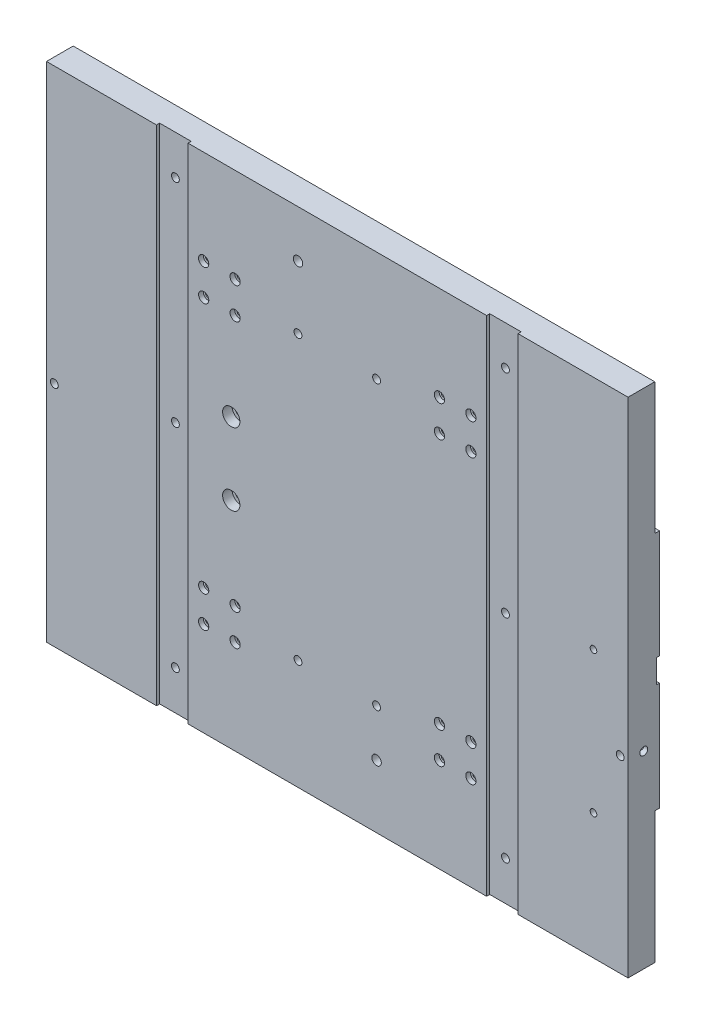
SolidWorks part; units mm, degrees
material "铝材"
ref_plane "前基準面" through (0, 0, 0) normal (0, 0, 1) x (1, 0, 0)
ref_plane "上基準面" through (0, 0, 0) normal (0, 1, 0) x (1, 0, 0)
ref_plane "右基準面" through (0, 0, 0) normal (1, 0, 0) x (0, 0, -1)
sketch "草图1" plane through (0, 0, 0) normal (0, 0, 1) x (1, 0, 0)
  line L1 (0, 0) -> (370, 0)
  line L2 (0, 0) -> (0, 320)
  line L3 (0, 320) -> (370, 320)
  line L4 (370, 0) -> (370, 320)
  dimension "D1" = 370
  dimension "D2" = 320
extrude "凸台-拉伸1" add sketch "草图1" along normal blind 20
sketch "草图2" plane through (370, 0, 0) normal (1, 0, 0) x (0, 0, -1)
  line L0 (0, 0) -> (0, 320) construction
  line L1 (0, 0) -> (-3, 0)
  line L2 (0, 0) -> (0, 83.6)
  line L3 (0, 83.6) -> (-3, 83.6)
  line L4 (-3, 0) -> (-3, 83.6)
  line L5 (0, 160) -> (-20, 160) construction
  line L6 (-20, 0) -> (-20, 320) construction
  line L7 (-3, 320) -> (-3, 236.4)
  line L8 (0, 236.4) -> (-3, 236.4)
  line L9 (0, 320) -> (0, 236.4)
  line L10 (0, 320) -> (-3, 320)
  dimension "D1" = 152.8
  dimension "D3" = 3
extrude "切除-拉伸1" cut sketch "草图2" against normal through all
sketch "草图3" plane through (0, 0, 0) normal (0, -1, 0) x (1, 0, 0)
  line L0 (0, 20) -> (370, 20) construction
  line L1 (230, 20) -> (140, 20)
  line L2 (230, 20) -> (230, 18)
  line L3 (230, 18) -> (140, 18)
  line L4 (140, 20) -> (140, 18)
  line L5 (185, 20) -> (185, 0) construction
  dimension "D1" = 2
  dimension "D2" = 90
extrude "切除-拉伸2" cut sketch "草图3" against normal through all
sketch "草图4" plane through (0, 0, 0) normal (0, -1, 0) x (1, 0, 0)
  line L0 (0, 20) -> (140, 20) construction
  line L1 (70, 20) -> (90, 20)
  line L2 (70, 20) -> (70, 18)
  line L3 (70, 18) -> (90, 18)
  line L4 (90, 20) -> (90, 18)
  line L5 (185, 3) -> (185, 18) construction
  line L6 (0, 3) -> (370, 3) construction
  line L7 (140, 18) -> (230, 18) construction
  line L8 (280, 20) -> (280, 18)
  line L9 (300, 18) -> (280, 18)
  line L10 (300, 20) -> (300, 18)
  line L11 (300, 20) -> (280, 20)
  dimension "D1" = 190
  dimension "D2" = 20
  dimension "D3" = 2
extrude "切除-拉伸3" cut sketch "草图4" against normal through all
sketch "草图5" plane through (370, 0, 0) normal (1, 0, 0) x (0, 0, -1)
  line L0 (0, 83.6) -> (0, 236.4) construction
  line L1 (0, 152.5) -> (-2, 152.5)
  line L2 (0, 152.5) -> (0, 167.5)
  line L3 (0, 167.5) -> (-2, 167.5)
  line L4 (-2, 152.5) -> (-2, 167.5)
  line L5 (0, 160) -> (-12.4315, 160) construction
  dimension "D1" = 2
  dimension "D2" = 15
sketch "草图6" plane through (0, 0, 18) normal (0, 0, 1) x (1, 0, 0)
  line L4 (140, 0) -> (230, 0)
  line L5 (230, 0) -> (230, 320)
  line L6 (230, 320) -> (140, 320)
  line L7 (140, 320) -> (140, 0)
  line L8 (140, 0) -> (230, 0)
  line L9 (230, 0) -> (230, 320)
  line L10 (230, 320) -> (140, 320)
  line L11 (140, 320) -> (140, 0)
  dimension "D1" = 0
extrude "凸台-拉伸2" add sketch "草图6" along normal up to surface (2 mm away) up to face at (255, 160, 20)
extrude "切除-拉伸4" cut sketch "草图5" against normal through all
sketch "草图7" plane through (0, 0, 0) normal (-1, 0, 0) x (0, 0, 1)
  line L0 (20, 320) -> (20, 0) construction
  line L1 (20, 0) -> (3, 0) construction
  circle A0 centre (10, 145) radius 2.5
  dimension "D2" = 5
  dimension "D3" = 145
  dimension "D1" = 10
extrude "切除-拉伸5" cut sketch "草图7" against normal blind 15
hole_wizard "M6 螺纹孔1" positions "草图9" profile "草图8" tap size "M6" standard "ISO"
sketch "草图9" plane through (0, 0, 20) normal (0, 0, 1) x (1, 0, 0)
  line L0 (0, 320) -> (0, 0) construction
  line L1 (0, 0) -> (70, 0) construction
  point P0 (5, 145)
  dimension "D1" = 5
  dimension "D2" = 145
sketch "草图8" plane through (5, 145, 20) normal (1, 0, 0) x (0, -1, 0)
  line L0 (0, 0) -> (0, 16.5022)
  line L1 (0, 16.5022) -> (2.5, 15)
  line L2 (2.5, 15) -> (2.5, 0)
  line L5 (2.5, 0) -> (0, 0)
  line L10 (0, 16.5022) -> (-2.5, 15) construction
  line L11 (0, -6.35) -> (0, 107.95) construction
  dimension "螺纹孔钻头直径" = 5
  dimension "螺纹孔钻头深度" = 15
  dimension "导头角度" = 118
cosmetic thread "孔螺蚊线1" parameters "D1"=12, "D2"=6
sketch "草图10" plane through (370, 0, 0) normal (1, 0, 0) x (0, 0, -1)
  line L0 (-20, 0) -> (-20, 320) construction
  line L1 (-20, 0) -> (-3, 0) construction
  circle A2 centre (-10, 120) radius 2.5
  dimension "D1" = 10
  dimension "D2" = 5
  dimension "D3" = 120
extrude "切除-拉伸6" cut sketch "草图10" against normal blind 15
hole_wizard "M6 螺纹孔2" positions "草图12" profile "草图11" tap size "M6" standard "ISO"
sketch "草图12" plane through (0, 0, 20) normal (0, 0, 1) x (1, 0, 0)
  line L0 (370, 0) -> (370, 320) construction
  line L1 (300, 0) -> (370, 0) construction
  point P0 (365, 120)
  dimension "D1" = 5
  dimension "D2" = 120
sketch "草图11" plane through (365, 120, 20) normal (1, 0, 0) x (0, -1, 0)
  line L0 (0, 0) -> (0, 16.5022)
  line L1 (0, 16.5022) -> (2.5, 15)
  line L2 (2.5, 15) -> (2.5, 0)
  line L5 (2.5, 0) -> (0, 0)
  line L10 (0, 16.5022) -> (-2.5, 15) construction
  line L11 (0, -6.35) -> (0, 107.95) construction
  dimension "螺纹孔钻头直径" = 5
  dimension "螺纹孔钻头深度" = 15
  dimension "导头角度" = 118
cosmetic thread "孔螺蚊线2" parameters "D1"=12, "D2"=6
sketch "草图13" plane through (0, 0, 20) normal (0, 0, 1) x (1, 0, 0)
  circle A0 centre (210, 40) radius 3
  circle A1 centre (160, 290) radius 3
extrude "切除-拉伸7" cut sketch "草图13" against normal through all
hole_wizard "M6 螺纹孔3" positions "草图15" profile "草图14" tap size "M6" standard "ISO"
sketch "草图15" plane through (0, 0, 20) normal (0, 0, 1) x (1, 0, 0)
  point P0 (160, 70)
  point P4 (210, 70)
  point P7 (160, 250)
  point P10 (210, 250)
  point P13 (290, 25)
  point P16 (290, 160)
  point P19 (290, 295)
  point P22 (80, 295)
  point P25 (80, 160)
  point P28 (80, 25)
sketch "草图14" plane through (160, 70, 20) normal (1, 0, 0) x (0, -1, 0)
  line L0 (0, 0) -> (0, 16.5022)
  line L1 (0, 16.5022) -> (2.5, 15)
  line L2 (2.5, 15) -> (2.5, 0)
  line L5 (2.5, 0) -> (0, 0)
  line L10 (0, 16.5022) -> (-2.5, 15) construction
  line L11 (0, -6.35) -> (0, 107.95) construction
  dimension "螺纹孔钻头直径" = 5
  dimension "螺纹孔钻头深度" = 15
  dimension "导头角度" = 118
cosmetic thread "孔螺蚊线3" parameters "D1"=12, "D2"=6
cosmetic thread "孔螺蚊线4" parameters "D1"=12, "D2"=6
cosmetic thread "孔螺蚊线5" parameters "D1"=12, "D2"=6
cosmetic thread "孔螺蚊线6" parameters "D1"=12, "D2"=6
cosmetic thread "孔螺蚊线7" parameters "D1"=12, "D2"=6
cosmetic thread "孔螺蚊线8" parameters "D1"=12, "D2"=6
cosmetic thread "孔螺蚊线9" parameters "D1"=12, "D2"=6
cosmetic thread "孔螺蚊线10" parameters "D1"=12, "D2"=6
cosmetic thread "孔螺蚊线11" parameters "D1"=12, "D2"=6
cosmetic thread "孔螺蚊线12" parameters "D1"=12, "D2"=6
hole_wizard "M3 六角凹头螺钉的柱形沉头孔1" positions "草图17" profile "草图16" counterbore size "M3" standard "ISO" end condition through all
sketch "草图17" plane through (0, 0, 20) normal (0, 0, 1) x (1, 0, 0)
  point P0 (270, 80)
  point P1 (250, 60)
  point P8 (250, 80)
  point P11 (270, 60)
  point P14 (120, 60)
  point P17 (100, 60)
  point P20 (100, 80)
  point P23 (120, 80)
sketch "草图16" plane through (270, 80, 20) normal (1, 0, 0) x (0, -1, 0)
  line L0 (0, 0) -> (0, 20)
  line L1 (0, 20) -> (1.8, 20)
  line L3 (1.8, 20) -> (1.8, 3)
  line L4 (1.8, 3) -> (3.25, 3)
  line L5 (3.25, 3) -> (3.25, 0)
  line L7 (3.25, 0) -> (0, 0)
  line L11 (0, -6.35) -> (0, 107.95) construction
  dimension "通孔孔直径" = 3.6
  dimension "通孔孔深度" = 20
  dimension "柱形沉头孔直径" = 6.5
  dimension "柱形沉头孔深度" = 3
hole_wizard "M3 六角凹头螺钉的柱形沉头孔2" positions "草图19" profile "草图18" counterbore size "M3" standard "ISO" end condition through all
sketch "草图19" plane through (0, 0, 20) normal (0, 0, 1) x (1, 0, 0)
  point P2 (100, 260)
  point P5 (270, 260)
  point P8 (250, 260)
  point P15 (250, 240)
  point P18 (270, 240)
  point P21 (120, 260)
  point P24 (100, 240)
  point P27 (120, 240)
sketch "草图18" plane through (100, 260, 20) normal (1, 0, 0) x (0, -1, 0)
  line L0 (0, 0) -> (0, 20)
  line L1 (0, 20) -> (1.8, 20)
  line L3 (1.8, 20) -> (1.8, 3)
  line L4 (1.8, 3) -> (3.25, 3)
  line L5 (3.25, 3) -> (3.25, 0)
  line L7 (3.25, 0) -> (0, 0)
  line L11 (0, -6.35) -> (0, 107.95) construction
  dimension "通孔孔直径" = 3.6
  dimension "通孔孔深度" = 20
  dimension "柱形沉头孔直径" = 6.5
  dimension "柱形沉头孔深度" = 3
hole_wizard "M5 螺纹孔1" positions "草图21" profile "草图20" tap size "M5" standard "ISO"
sketch "草图21" plane through (0, 0, 2) normal (0, 0, -1) x (-1, 0, 0)
  point P0 (-264, 160)
  point P1 (-183, 160)
  point P4 (-21, 160)
  point P10 (-102, 160)
sketch "草图20" plane through (264, 160, 2) normal (1, 0, 0) x (0, 1, 0)
  line L0 (0, 0) -> (0, 13.6618)
  line L1 (0, 13.6618) -> (2.1, 12.4)
  line L2 (2.1, 12.4) -> (2.1, 0)
  line L5 (2.1, 0) -> (0, 0)
  line L10 (0, 13.6618) -> (-2.1, 12.4) construction
  line L11 (0, -6.35) -> (0, 107.95) construction
  dimension "螺纹孔钻头直径" = 4.2
  dimension "螺纹孔钻头深度" = 12.4
  dimension "导头角度" = 118
cosmetic thread "孔螺蚊线13" parameters "D1"=10, "D2"=5
cosmetic thread "孔螺蚊线14" parameters "D1"=10, "D2"=5
cosmetic thread "孔螺蚊线15" parameters "D1"=10, "D2"=5
cosmetic thread "孔螺蚊线16" parameters "D1"=10, "D2"=5
hole_wizard "M4 螺纹孔2" positions "草图25" profile "草图24" tap size "M4" standard "ISO"
sketch "草图25" plane through (0, 0, 0) normal (0, 0, -1) x (-1, 0, 0)
  line L0 (0, 320) -> (-370, 320) construction
  line L1 (-370, 167.5) -> (-370, 236.4) construction
  point P0 (-117, 220.5)
  point P1 (-127, 220.5)
  point P3 (-244, 220.5)
  point P5 (-254, 220.5)
  dimension "D1" = 10
  dimension "D2" = 10
  dimension "D3" = 99.5
  dimension "D4" = 116
  dimension "D5" = 243
sketch "草图24" plane through (117, 220.5, 0) normal (1, 0, 0) x (0, 1, 0)
  line L0 (0, 0) -> (0, 11.0914)
  line L1 (0, 11.0914) -> (1.65, 10.1)
  line L2 (1.65, 10.1) -> (1.65, 0)
  line L5 (1.65, 0) -> (0, 0)
  line L10 (0, 11.0914) -> (-1.65, 10.1) construction
  line L11 (0, -6.35) -> (0, 107.95) construction
  dimension "螺纹孔钻头直径" = 3.3
  dimension "螺纹孔钻头深度" = 10.1
  dimension "导头角度" = 118
cosmetic thread "孔螺蚊线21" parameters "D1"=8, "D2"=4
cosmetic thread "孔螺蚊线22" parameters "D1"=8, "D2"=4
cosmetic thread "孔螺蚊线23" parameters "D1"=8, "D2"=4
cosmetic thread "孔螺蚊线24" parameters "D1"=8, "D2"=4
hole_wizard "M4 螺纹孔3" positions "草图27" profile "草图26" tap size "M4" standard "ISO"
sketch "草图27" plane through (0, 0, 3) normal (0, 0, -1) x (-1, 0, 0)
  line L0 (0, 0) -> (-370, 0) construction
  line L1 (-370, 83.6) -> (-370, 0) construction
  point P0 (-253, 40.5)
  point P1 (-243, 40.5)
  point P3 (-128, 40.5)
  point P5 (-118, 40.5)
  dimension "D1" = 10
  dimension "D2" = 10
  dimension "D3" = 40.5
  dimension "D4" = 117
  dimension "D5" = 242
sketch "草图26" plane through (253, 40.5, 3) normal (1, 0, 0) x (0, 1, 0)
  line L0 (0, 0) -> (0, 11.0914)
  line L1 (0, 11.0914) -> (1.65, 10.1)
  line L2 (1.65, 10.1) -> (1.65, 0)
  line L5 (1.65, 0) -> (0, 0)
  line L10 (0, 11.0914) -> (-1.65, 10.1) construction
  line L11 (0, -6.35) -> (0, 107.95) construction
  dimension "螺纹孔钻头直径" = 3.3
  dimension "螺纹孔钻头深度" = 10.1
  dimension "导头角度" = 118
cosmetic thread "孔螺蚊线25" parameters "D1"=8, "D2"=4
cosmetic thread "孔螺蚊线26" parameters "D1"=8, "D2"=4
cosmetic thread "孔螺蚊线27" parameters "D1"=8, "D2"=4
cosmetic thread "孔螺蚊线28" parameters "D1"=8, "D2"=4
hole_wizard "M5 螺纹孔2" positions "草图29" profile "草图28" tap size "M5" standard "ISO"
sketch "草图29" plane through (0, 0, 20) normal (0, 0, 1) x (1, 0, 0)
  point P0 (348, 80)
  point P1 (348, 170)
sketch "草图28" plane through (348, 80, 20) normal (1, 0, 0) x (0, -1, 0)
  line L0 (0, 0) -> (0, 13.6618)
  line L1 (0, 13.6618) -> (2.1, 12.4)
  line L2 (2.1, 12.4) -> (2.1, 0)
  line L5 (2.1, 0) -> (0, 0)
  line L10 (0, 13.6618) -> (-2.1, 12.4) construction
  line L11 (0, -6.35) -> (0, 107.95) construction
  dimension "螺纹孔钻头直径" = 4.2
  dimension "螺纹孔钻头深度" = 12.4
  dimension "导头角度" = 118
cosmetic thread "孔螺蚊线29" parameters "D1"=10, "D2"=5
cosmetic thread "孔螺蚊线30" parameters "D1"=10, "D2"=5
sketch "草图30" plane through (0, 83.6, 0) normal (0, -1, 0) x (1, 0, 0)
  line L0 (0, 0) -> (370, 0) construction
  line L1 (110, 3) -> (125.1, 3)
  line L2 (110, 3) -> (110, 0)
  line L3 (110, 0) -> (125.1, 0)
  line L4 (125.1, 3) -> (125.1, 0)
  line L6 (0, 20) -> (0, 3) construction
  line L7 (0, 3) -> (370, 3) construction
  dimension "D1" = 15.1
  dimension "D2" = 110
extrude "切除-拉伸8" cut sketch "草图30" against normal through all
hole_wizard "M6 六角凹头螺钉的柱形沉头孔1" positions "草图32" profile "草图31" counterbore size "M6" standard "ISO" end condition through all
sketch "草图32" plane through (0, 0, 20) normal (0, 0, 1) x (1, 0, 0)
  point P1 (117.55, 137)
  point P4 (117.55, 183)
sketch "草图31" plane through (117.55, 137, 20) normal (1, 0, 0) x (0, -1, 0)
  line L0 (0, 0) -> (0, 20)
  line L1 (0, 20) -> (3.3, 20)
  line L3 (3.3, 20) -> (3.3, 6)
  line L4 (3.3, 6) -> (5.5, 6)
  line L5 (5.5, 6) -> (5.5, 0)
  line L7 (5.5, 0) -> (0, 0)
  line L11 (0, -6.35) -> (0, 107.95) construction
  dimension "通孔孔直径" = 6.6
  dimension "通孔孔深度" = 20
  dimension "柱形沉头孔直径" = 11
  dimension "柱形沉头孔深度" = 6
